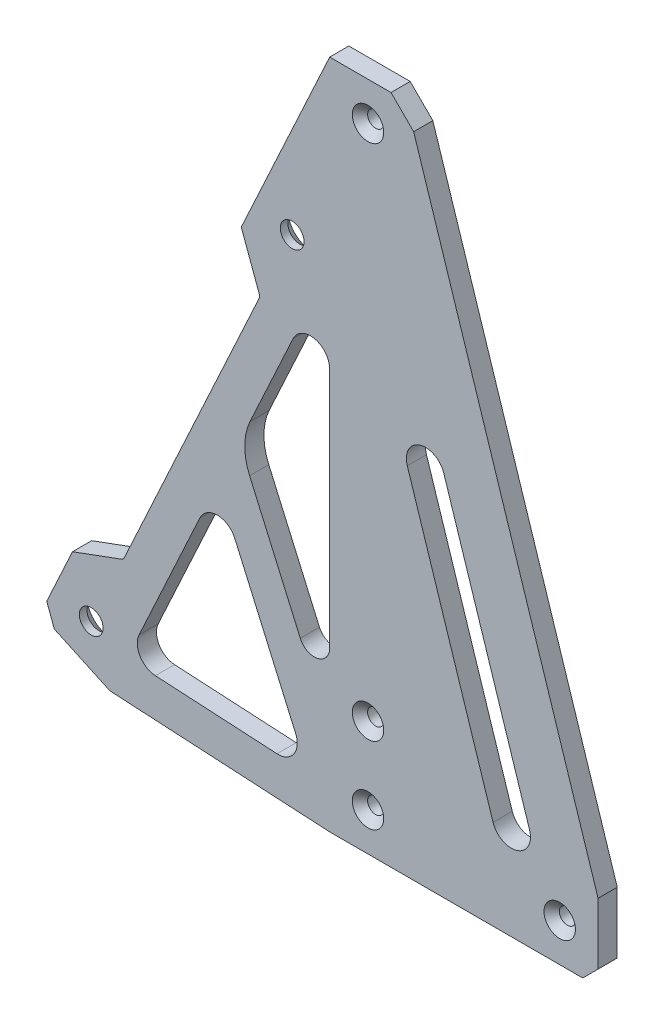
SolidWorks part; units mm, degrees
ref_plane "前视基准面" through (0, 0, 0) normal (0, 0, 1) x (1, 0, 0)
ref_plane "上视基准面" through (0, 0, 0) normal (0, 1, 0) x (1, 0, 0)
ref_plane "右视基准面" through (0, 0, 0) normal (1, 0, 0) x (0, 0, -1)
sketch "草图1" plane through (0, 0, 0) normal (0, 0, 1) x (1, 0, 0)
  line L0 (-35, 87.5) -> (-35, -87.5)
  line L1 (-35, -87.5) -> (35, -87.5)
  line L2 (35, -87.5) -> (35, -67.5)
  line L3 (35, -67.5) -> (-15, 87.5)
  line L4 (-15, 87.5) -> (-35, 87.5)
  line L5 (25, -77.5) -> (-25, -77.5) construction
  line L6 (-25, -77.5) -> (-25, -57.5) construction
  line L7 (-25, -57.5) -> (-25, 77.5) construction
  circle A0 centre (-25, -77.5) radius 2.1
  circle A1 centre (25, -77.5) radius 2.1
  circle A2 centre (-25, 77.5) radius 2.1
  circle A3 centre (-25, -57.5) radius 2.1
  point P0 (-35, 0)
  point P7 (0, -87.5)
  dimension "D3" = 10
  dimension "D6" = 10
  dimension "D7" = 4.2
  dimension "D1" = 20
  dimension "D2" = 20
  dimension "D4" = 10
  dimension "D5" = 10
  dimension "D8" = 175
  dimension "D9" = 70
  dimension "D10" = 20
extrude "凸台-拉伸1" add sketch "草图1" along normal mid plane 5
sketch "草图2" plane through (0, 0, -2.5) normal (0, 0, -1) x (-1, 0, 0)
  line L0 (-12.3723, -62.5) -> (10, 6.854) construction
  line L1 (-17.1308, -60.965) -> (5.2415, 8.389)
  line L2 (-7.6137, -64.035) -> (14.7585, 5.319)
  line L3 (-35, -67.5) -> (15, 87.5) construction
  line L5 (35, 87.5) -> (35, -87.5) construction
  arc A0 (-17.1308, -60.965) -> (-7.6137, -64.035) centre (-12.3723, -62.5) ccw
  arc A1 (14.7585, 5.319) -> (5.2415, 8.389) centre (10, 6.854) ccw
  circle A3 centre (-25, -77.5) radius 2.1 construction
  point P2 (-1.1861, -27.823)
  dimension "D2" = 5
  dimension "D3" = 25
  dimension "D4" = 15
  dimension "D1" = 15
extrude "切除-拉伸1" cut sketch "草图2" against normal through all
sketch "草图3" plane through (0, 0, -2.5) normal (0, 0, -1) x (-1, 0, 0)
  line L0 (35, -87.5) -> (92.3029, -84.3033)
  line L1 (92.3029, -84.3033) -> (110.4606, -75.9188)
  line L2 (110.4606, -75.9188) -> (35, 87.5)
  line L3 (110.4606, -75.9188) -> (115, -73.8227) construction
  line L6 (115, -73.8227) -> (39.5394, 89.5961) construction
  line L7 (39.5394, 89.5961) -> (35, 87.5) construction
  line L8 (35, 87.5) -> (35, -87.5) construction
  line L9 (15, 87.5) -> (35, 87.5) construction
  line L10 (35, 87.5) -> (35, -87.5)
  dimension "D1" = 5
  dimension "D2" = 80
  dimension "D3" = 180
  dimension "D4" = 20
extrude "凸台-拉伸2" add sketch "草图3" against normal blind 5
sketch "草图5" plane through (0, 0, -2.5) normal (0, 0, -1) x (-1, 0, 0)
  line L0 (35, 39.793) -> (58.5981, -11.3116)
  line L1 (87.7943, -74.5393) -> (40.598, -77.1722)
  line L2 (35, -65.049) -> (35, 39.793)
  line L3 (35, -87.5) -> (92.3029, -84.3033) construction
  line L4 (110.4606, -75.9188) -> (35, 87.5) construction
  line L5 (35, -77.4845) -> (61.3971, -17.3731) construction
  line L6 (40.598, -77.1722) -> (64.1961, -23.4347)
  line L7 (35, -65.049) -> (58.5981, -11.3116)
  line L8 (30.422, -75.4741) -> (56.8191, -15.3628) construction
  line L9 (39.578, -79.4948) -> (65.9752, -19.3835) construction
  line L10 (64.1961, -23.4347) -> (87.7943, -74.5393)
  circle A0 centre (25, -57.5) radius 2.1 construction
  dimension "D1" = 20
  dimension "D2" = 10
  dimension "D3" = 10
  dimension "D4" = 5
  dimension "D5" = 5
extrude "切除-拉伸2" cut sketch "草图5" against normal through all
fillet "圆角1" radius 5 4 edges at (-87.7943, -74.5393, 0) (-64.1961, -23.4347, 0) (-40.598, -77.1722, 0) (-35, 39.793, 0)
fillet "圆角2" radius 4 1 edges at (-35, -65.049, 0)
fillet "圆角3" radius 15 1 edges at (-58.5981, -11.3116, 0)
chamfer "倒角1" distance 4 angle 45 3 edges at (35, -87.5, 0) (-110.4606, -75.9188, 0) (-15, 87.5, 0)
chamfer "倒角2" distance 2 angle 45 4 edges at (-22.9, 77.5, 2.5) (27.1, -77.5, 2.5) (-22.9, -57.5, 2.5) (-22.9, -77.5, 2.5)
sketch "草图6" plane through (0, 0, -2.5) normal (0, 0, -1) x (-1, 0, 0)
  line L0 (44.7863, 42.453) -> (97.1895, -71.0322) construction
  line L2 (108.7837, -72.2873) -> (35, 87.5) construction
  line L3 (92.3029, -84.3033) -> (106.8291, -77.5957) construction
  line L4 (44.5394, 19.1343) -> (35, 39.793) construction
  line L5 (35, 17.0381) -> (35, 39.793) construction
  line L6 (55.7658, -5.1779) -> (44.5394, 19.1343) construction
  line L7 (35, 39.793) -> (53.1576, 48.1775) construction
  circle A0 centre (97.1895, -71.0322) radius 3.1
  circle A2 centre (44.7863, 42.453) radius 3.1
  dimension "D1" = 10
  dimension "D2" = 10
  dimension "D4" = 6.2
  dimension "D3" = 125
extrude "切除-拉伸3" cut sketch "草图6" against normal through all
sketch "草图7" plane through (0, 0, 2.5) normal (0, 0, 1) x (1, 0, 0)
  line L0 (-58.0574, 37.5665) -> (-53.1708, 24.2954)
  line L1 (-108.7837, -72.2873) -> (-35, 87.5) construction
  line L2 (-53.1708, 24.2954) -> (-88.805, -52.8746)
  line L3 (-88.805, -52.8746) -> (-102.0761, -57.7611)
  line L4 (-102.0761, -57.7611) -> (-58.0574, 37.5665)
  line L6 (-55.7658, -5.1779) -> (-44.5394, 19.1343) construction
  line L7 (-102.0761, -57.7611) -> (-83.9184, -66.1457) construction
  line L8 (-84.7104, -67.8606) -> (-68.8501, -33.5133) construction
  line L9 (-58.0574, 37.5665) -> (-39.8998, 29.182) construction
  circle A4 centre (-44.7863, 42.453) radius 3.1 construction
  circle A5 centre (-97.1895, -71.0322) radius 3.1 construction
  dimension "D2" = 10
  dimension "D3" = 10
  dimension "D1" = 10
extrude "切除-拉伸4" cut sketch "草图7" against normal through all
chamfer "倒角3" distance 3 angle 45 2 edges at (-100.2895, -71.0322, -2.5) (-47.8863, 42.453, -2.5)
fillet "圆角4" radius 1 2 edges at (-88.805, -52.8746, 0) (-53.1708, 24.2954, 0)
